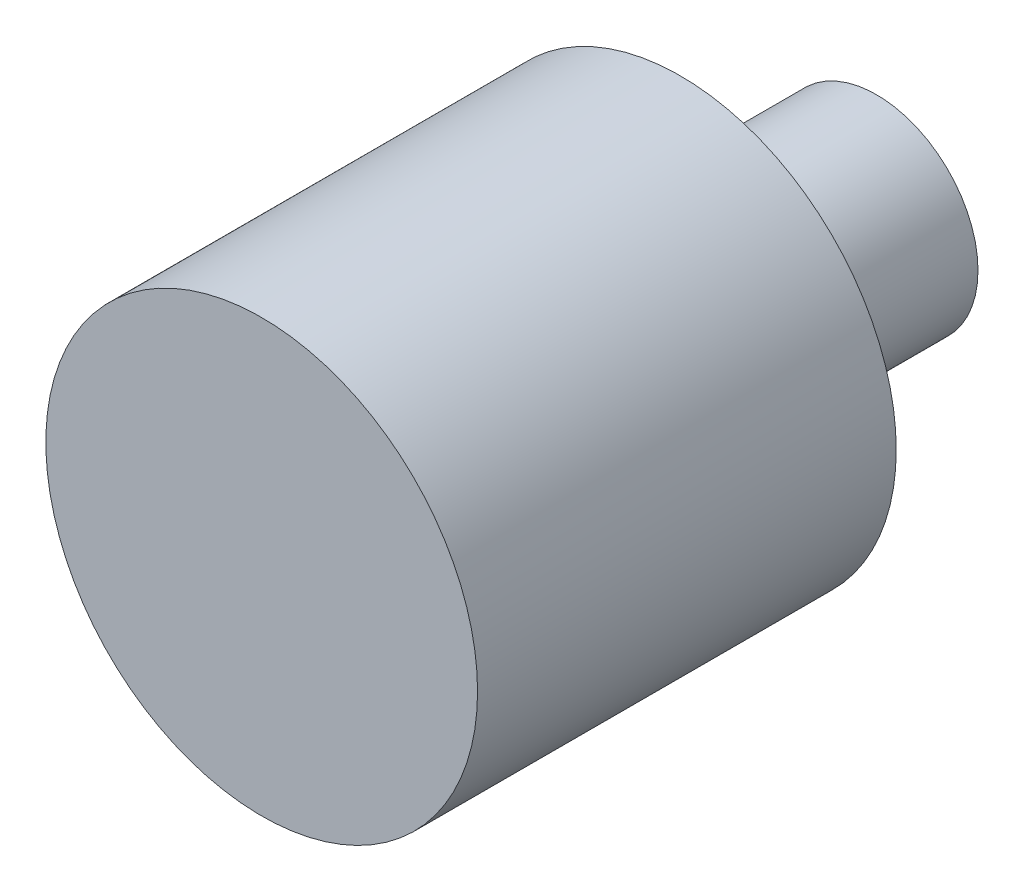
SolidWorks part; units mm, degrees
ref_plane "前视基准面" through (0, 0, 0) normal (0, 0, 1) x (1, 0, 0)
ref_plane "上视基准面" through (0, 0, 0) normal (0, 1, 0) x (1, 0, 0)
ref_plane "右视基准面" through (0, 0, 0) normal (1, 0, 0) x (0, 0, -1)
sketch "草图1" plane through (0, 0, 0) normal (0, 0, 1) x (1, 0, 0)
  circle A0 centre (0, 0) radius 16.5
  dimension "D1" = 33
extrude "凸台-拉伸1" add sketch "草图1" along normal blind 32
sketch "草图2" plane through (0, 0, 0) normal (0, 0, -1) x (-1, 0, 0)
  circle A0 centre (0, 0) radius 3
  dimension "D1" = 6
extrude "凸台-拉伸2" add sketch "草图2" along normal blind 15
hole_wizard "M3 螺纹孔1" positions "草图4" profile "草图3" tap size "M3" standard "GB"
sketch "草图4" plane through (0, 0, 0) normal (0, 0, -1) x (-1, 0, 0)
  circle A0 centre (0, 0) radius 12.5 construction
  point P5 (0, 12.5)
  point P7 (12.5, 0)
  point P9 (0, -12.5)
  point P11 (-12.5, 0)
  dimension "D1" = 25
sketch "草图3" plane through (0, 12.5, 0) normal (1, 0, 0) x (0, 1, 0)
  line L0 (0, 0) -> (0, 4.7511)
  line L1 (0, 4.7511) -> (1.25, 4)
  line L2 (1.25, 4) -> (1.25, 0)
  line L5 (1.25, 0) -> (0, 0)
  line L10 (0, 4.7511) -> (-1.25, 4) construction
  line L11 (0, -6.35) -> (0, 107.95) construction
  dimension "螺纹孔钻头直径" = 2.5
  dimension "螺纹孔钻头深度" = 4
  dimension "导头角度" = 118
cosmetic thread "孔螺蚊线1" parameters "D1"=4, "D2"=3
cosmetic thread "孔螺蚊线2" parameters "D1"=4, "D2"=3
cosmetic thread "孔螺蚊线3" parameters "D1"=4, "D2"=3
cosmetic thread "孔螺蚊线4" parameters "D1"=4, "D2"=3
sketch "草图5" plane through (0, 0, -15) normal (0, 0, -1) x (-1, 0, 0)
  circle A0 centre (0, 0) radius 7.75
  dimension "D1" = 15.5
extrude "凸台-拉伸3" add sketch "草图5" against normal blind 11
move or copy body "实体-移动/复制1" [suppressed] bodies to move or copy 108
